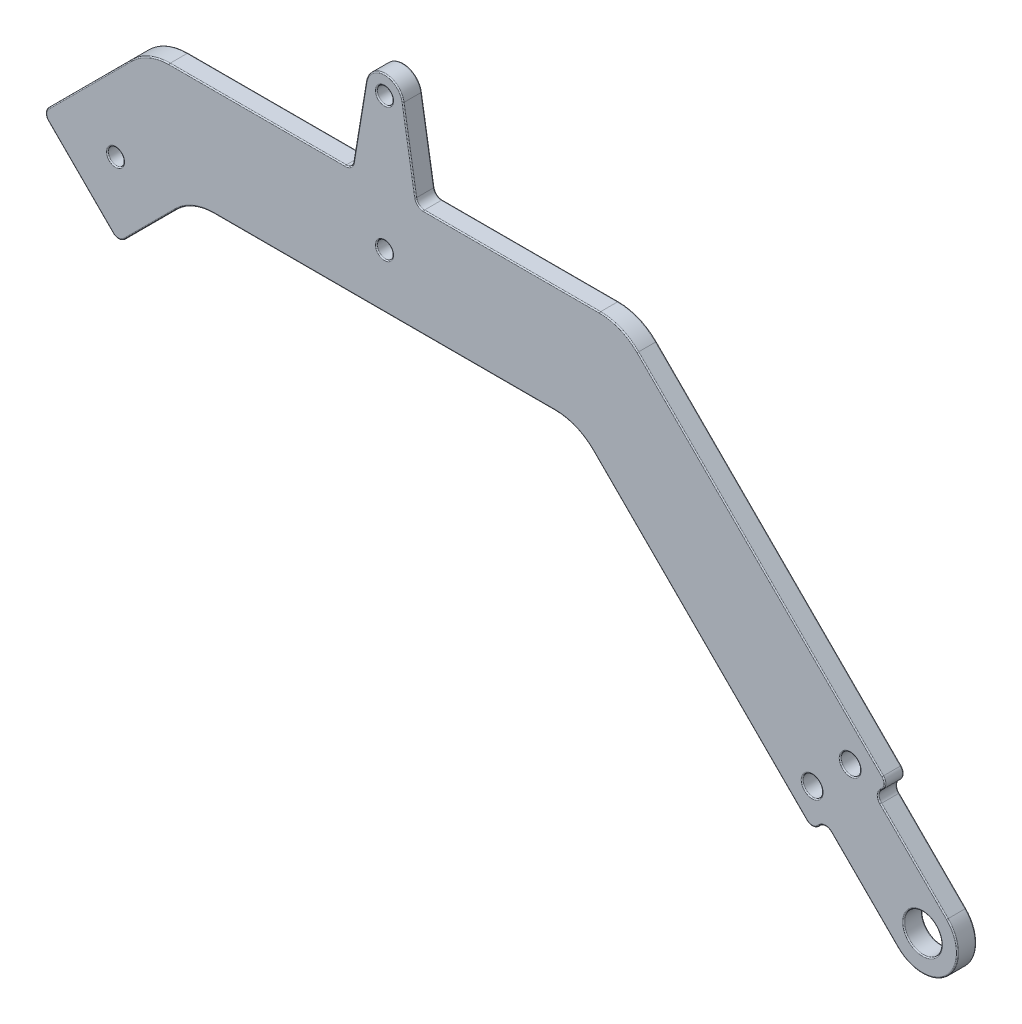
SolidWorks part; units mm, degrees
ref_plane "Front Plane" through (0, 0, 0) normal (0, 0, 1) x (1, 0, 0)
ref_plane "Top Plane" through (0, 0, 0) normal (0, 1, 0) x (1, 0, 0)
ref_plane "Right Plane" through (0, 0, 0) normal (1, 0, 0) x (0, 0, -1)
sketch "Sketch1" plane through (0, 0, 0) normal (0, 0, 1) x (1, 0, 0)
  line L0 (-100, 0) -> (100, 0) construction
  line L1 (-100, 0) -> (0, 100) construction
  line L2 (0, 100) -> (100, 0) construction
  line L3 (0, 0) -> (-50, 50) construction
  line L4 (-50, 50) -> (0, 0) construction
  line L5 (-40, 60) -> (40, 60) construction
  line L6 (0, 100) -> (0, 60) construction
  circle A0 centre (-100, 0) radius 20
  circle A1 centre (0, 0) radius 20
  circle A2 centre (100, 0) radius 20
  point P5 (0, 0)
  dimension "D5" = 40
  dimension "D1" = 200
  dimension "D2" = 90
  dimension "D3" = 90
  dimension "D4" = 80
sketch "Sketch2" plane through (0, 0, 0) normal (0, 0, 1) x (1, 0, 0)
  line L0 (-56.5165, 43.4835) -> (-40, 60) construction
  line L1 (-100, 0) -> (0, 100) construction
  line L2 (-40, 60) -> (40, 60) construction
  line L3 (40, 60) -> (86.565, 13.435) construction
  line L4 (0, 100) -> (100, 0) construction
  line L5 (-49.4454, 36.4124) -> (-35.8579, 50)
  line L6 (-35.8579, 50) -> (35.8579, 50)
  line L7 (35.8579, 50) -> (79.4939, 6.364)
  line L8 (-63.5876, 50.5546) -> (-44.1421, 70)
  line L9 (-44.1421, 70) -> (44.1421, 70)
  line L10 (44.1421, 70) -> (93.636, 20.5061)
  line L11 (-63.5876, 50.5546) -> (-49.4454, 36.4124)
  line L12 (93.636, 20.5061) -> (79.4939, 6.364)
  line L13 (81.9688, 8.8388) -> (95.4038, -4.5962)
  line L14 (91.1612, 18.0312) -> (104.5962, 4.5962)
  line L15 (75.9584, 9.8995) -> (90.1005, 24.0416) construction
  line L16 (0, 100) -> (0, 60) construction
  line L17 (-6, 70) -> (-3.4326, 85.5452)
  line L18 (6, 70) -> (3.4532, 85.4203)
  circle A0 centre (100, 0) radius 3.5
  circle A1 centre (100, 0) radius 10 construction
  arc A2 (95.4038, -4.5962) -> (104.5962, 4.5962) centre (100, 0) ccw
  circle A3 centre (100, 0) radius 0.5
  circle A4 centre (100, 0) radius 6.5 construction
  circle A5 centre (79.4939, 13.435) radius 1.8428
  circle A6 centre (86.565, 20.5061) radius 1.8428
  circle A7 centre (0, 60) radius 1.5
  circle A8 centre (0, 84.85) radius 1.5
  arc A9 (3.4532, 85.4203) -> (-3.4532, 85.4203) centre (0, 84.85) ccw
  circle A10 centre (0, 84.85) radius 3.5 construction
  circle A11 centre (-50, 50) radius 1.5
  dimension "D4" = 20
  dimension "D5" = 7
  dimension "D11" = 3
  dimension "D15" = 3
  dimension "D3" = 27.5
  dimension "D8" = 19
  dimension "D9" = 5
  dimension "D10" = 5
  dimension "5" = 5
  dimension "D12" = 14.85
  dimension "D7" = 6
  dimension "D14" = 6
  dimension "D1" = 10
  dimension "D2" = 10
  dimension "D6" = 3
  dimension "D13" = 2
sketch "Sketch3" plane through (0, 0, 0) normal (0, 0, 1) x (1, 0, 0)
  line L0 (-100, 0) -> (100, 0) construction
  line L1 (-86.6719, 13.3281) -> (-50, 50) construction
  line L2 (-24.0416, 9.8995) -> (-9.8995, 24.0416) construction
  line L3 (-50, 50) -> (-13.435, 13.435) construction
  line L4 (0, 0) -> (-50, 50) construction
  line L5 (-79.4939, 6.364) -> (-50, 35.8579)
  line L6 (-50, 35.8579) -> (-20.5061, 6.364)
  line L7 (-93.636, 20.5061) -> (-50, 64.1421)
  line L8 (-50, 64.1421) -> (-6.364, 20.5061)
  line L9 (-81.6799, 4.1779) -> (-50, 35.8579) construction
  line L10 (-95.8221, 18.3201) -> (-50, 64.1421) construction
  line L11 (-93.636, 20.5061) -> (-79.4939, 6.364)
  line L12 (-20.5061, 6.364) -> (-6.364, 20.5061)
  line L13 (-81.9688, 8.8388) -> (-95.4038, -4.5962)
  line L14 (-91.1612, 18.0312) -> (-104.5962, 4.5962)
  line L15 (-18.0312, 8.8388) -> (-4.5962, -4.5962)
  line L16 (-8.8388, 18.0312) -> (4.5962, 4.5962)
  line L17 (-88.751, 11.249) -> (-50, 50) construction
  line L18 (-90.1005, 24.0416) -> (-76.1469, 10.088) construction
  circle A0 centre (-100, 0) radius 10 construction
  circle A1 centre (-100, 0) radius 3.5
  circle A2 centre (0, 0) radius 10 construction
  circle A3 centre (0, 0) radius 3.5
  arc A4 (-4.5962, -4.5962) -> (4.5962, 4.5962) centre (0, 0) ccw
  arc A5 (-104.5962, 4.5962) -> (-95.4038, -4.5962) centre (-100, 0) ccw
  circle A6 centre (-86.565, 20.5061) radius 1
  circle A7 centre (0, 0) radius 6.5 construction
  circle A8 centre (-100, 0) radius 6.5 construction
  circle A9 centre (-79.4939, 13.435) radius 1
  circle A10 centre (-20.5061, 13.435) radius 1
  circle A11 centre (-13.435, 20.5061) radius 1
  circle A12 centre (-50, 50) radius 1.5 construction
  circle A13 centre (-50, 50) radius 1.5
  dimension "D1" = 20
  dimension "D2" = 7
  dimension "D9" = 2
  dimension "D7" = 19
  dimension "D8" = 19
  dimension "D10" = 5
  dimension "D11" = 5
  dimension "D12" = 5
  dimension "D13" = 5
  dimension "D14" = 5
  dimension "D15" = 5
  dimension "D3" = 3
  dimension "D4" = 3
  dimension "D5" = 10
  dimension "D6" = 10
sketch "Sketch4" plane through (0, 0, 0) normal (0, 0, 1) x (1, 0, 0)
  line L1 (57.5, 96.35) -> (57.5, 86.35)
  line L2 (57.5, 86.35) -> (44.1421, 70)
  line L3 (44.1421, 70) -> (-44.1421, 70)
  line L4 (-44.1421, 70) -> (-57.5, 86.35)
  line L5 (-57.5, 86.35) -> (-57.5, 96.35)
  line L7 (-57.5, 96.35) -> (57.5, 96.35)
  line L8 (-4, 60) -> (-4, 70)
  line L9 (4, 60) -> (4, 70)
  line L10 (-22.4799, 87.85) -> (22.5201, 87.85) construction
  line L11 (-22.4799, 92.35) -> (22.5201, 92.35)
  line L12 (-22.4799, 83.35) -> (22.5201, 83.35)
  circle A0 centre (0, 60) radius 1.5 construction
  circle A1 centre (0, 60) radius 1.5
  arc A2 (-4, 60) -> (4, 60) centre (0, 60) ccw
  circle A3 centre (0, 60) radius 4 construction
  arc A4 (-22.4799, 92.35) -> (-22.4799, 83.35) centre (-22.4799, 87.85) ccw
  arc A5 (22.5201, 83.35) -> (22.5201, 92.35) centre (22.5201, 87.85) ccw
  circle A6 centre (0, 84.85) radius 1.5 construction
  point P0 (0, 96.35)
  point P22 (0.0201, 87.85)
  dimension "D1" = 115
  dimension "D2" = 10
  dimension "D4" = 45
  dimension "D5" = 9
  dimension "D6" = 45
  dimension "D7" = 4
  dimension "D3" = 2.5
sketch "Sketch6" plane through (0, 0, 0) normal (0, 0, 1) x (1, 0, 0)
  line L0 (81.9688, 8.8388) -> (95.4038, -4.5962) construction
  line L1 (91.1612, 18.0312) -> (104.5962, 4.5962) construction
  line L2 (6, 70) -> (3.4532, 85.4203) construction
  line L3 (-6, 70) -> (-3.4326, 85.5452) construction
  line L4 (81.9688, 8.8388) -> (95.4038, -4.5962)
  line L5 (91.1612, 18.0312) -> (104.5962, 4.5962)
  line L6 (6, 70) -> (3.4532, 85.4203)
  line L7 (-6, 70) -> (-3.4326, 85.5452)
  line L8 (93.636, 20.5061) -> (44.1421, 70)
  line L9 (79.4939, 6.364) -> (93.636, 20.5061)
  line L10 (35.8579, 50) -> (79.4939, 6.364)
  line L11 (-35.8579, 50) -> (35.8579, 50)
  line L12 (-49.4454, 36.4124) -> (-35.8579, 50)
  line L13 (-63.5876, 50.5546) -> (-49.4454, 36.4124)
  line L14 (-44.1421, 70) -> (-63.5876, 50.5546)
  line L15 (44.1421, 70) -> (-44.1421, 70)
  line L16 (93.636, 20.5061) -> (44.1421, 70)
  line L17 (79.4939, 6.364) -> (81.9688, 8.8388)
  line L18 (35.8579, 50) -> (79.4939, 6.364)
  line L19 (-35.8579, 50) -> (35.8579, 50)
  line L20 (-49.4454, 36.4124) -> (-35.8579, 50)
  line L21 (-63.5876, 50.5546) -> (-49.4454, 36.4124)
  line L22 (-44.1421, 70) -> (-63.5876, 50.5546)
  line L23 (44.1421, 70) -> (6, 70)
  line L24 (-6, 70) -> (-44.1421, 70)
  line L25 (91.1612, 18.0312) -> (93.636, 20.5061)
  arc A0 (95.4038, -4.5962) -> (104.5962, 4.5962) centre (100, 0) ccw construction
  circle A1 centre (100, 0) radius 0.5
  circle A2 centre (100, 0) radius 0.5
  circle A3 centre (100, 0) radius 3.5
  circle A4 centre (100, 0) radius 3.5
  circle A5 centre (0, 84.85) radius 1.5
  circle A6 centre (0, 84.85) radius 1.5
  circle A7 centre (0, 60) radius 1.5
  circle A8 centre (0, 60) radius 1.5
  circle A9 centre (86.565, 20.5061) radius 1.8428
  circle A10 centre (86.565, 20.5061) radius 1.8428
  circle A11 centre (79.4939, 13.435) radius 1.8428
  circle A12 centre (79.4939, 13.435) radius 1.8428
  circle A13 centre (-50, 50) radius 1.5
  circle A14 centre (-50, 50) radius 1.5
  arc A15 (3.4532, 85.4203) -> (-3.4532, 85.4203) centre (0, 84.85) ccw construction
  arc A16 (95.4038, -4.5962) -> (104.5962, 4.5962) centre (100, 0) ccw
  arc A17 (3.4532, 85.4203) -> (-3.4532, 85.4203) centre (0, 84.85) ccw
  dimension "D1" = 0
  dimension "D2" = 0
  dimension "D3" = 0
  dimension "D4" = 0
  dimension "D5" = 0
  dimension "D6" = 0
  dimension "D7" = 0
  dimension "D8" = 0
extrude "Boss-Extrude1" add sketch "Sketch6" along normal blind 3.5 contours L6 A17 L7 L24 L22 L21 L20 L19 L18 L17 L4 A16 L5 L25 L16 L23 A4 A6 A8 A10 A12 A14
fillet "Fillet1" radius 10 4 edges at (-35.8579, 50, 1.75) (35.8579, 50, 1.75) (-44.1421, 70, 1.75) (44.1421, 70, 1.75)
fillet "Fillet2" radius 1.5 8 edges at (-49.4454, 36.4124, 1.75) (-63.5876, 50.5546, 1.75) (-6, 70, 1.75) (6, 70, 1.75) (81.9688, 8.8388, 1.75) (79.4939, 6.364, 1.75) (91.1612, 18.0312, 1.75) (93.636, 20.5061, 1.75)
fillet "Fillet3" radius 0.2 68 edges at (103.5, 0, 0) (1.5, 84.85, 0) (1.5, 60, 0) (88.4078, 20.5061, 0) (81.3367, 13.435, 0) (-48.5, 50, 0) (4.6229, 78.3379, 0) (0, 88.35, 0) (-4.6229, 78.3379, 0) (-23.6363, 70, 0) (-54.799, 59.3431, 0) (-56.5165, 43.4835, 0) (-43.5858, 42.2721, 0) (0, 50, 0) (58.61, 27.2478, 0) (80.7313, 7.6014, 0) (89.2166, 1.591, 0) (104.5962, -4.5962, 0) (98.409, 10.7834, 0) (92.3986, 19.2687, 0) (69.8232, 44.3189, 0) (23.6363, 70, 0) (103.5, 0, 3.5) (1.5, 84.85, 3.5) (1.5, 60, 3.5) (88.4078, 20.5061, 3.5) (81.3367, 13.435, 3.5) (-48.5, 50, 3.5) (4.6229, 78.3379, 3.5) (0, 88.35, 3.5) (-4.6229, 78.3379, 3.5) (-23.6363, 70, 3.5) (-54.799, 59.3431, 3.5) (-56.5165, 43.4835, 3.5) (-43.5858, 42.2721, 3.5) (0, 50, 3.5) (58.61, 27.2478, 3.5) (80.7313, 7.6014, 3.5) (89.2166, 1.591, 3.5) (104.5962, -4.5962, 3.5) (98.409, 10.7834, 3.5) (92.3986, 19.2687, 3.5) (69.8232, 44.3189, 3.5) (43.8268, 69.2388, 0) (-43.8268, 69.2388, 0) (43.8268, 69.2388, 3.5) (-43.8268, 69.2388, 3.5) (-35.5426, 49.2388, 0) (-35.5426, 49.2388, 3.5) (35.5426, 49.2388, 0) (35.5426, 49.2388, 3.5) (93.0147, 20.5061, 0) (79.4939, 6.9853, 0) (-62.9663, 50.5546, 0) (-49.4454, 37.0337, 0) (93.0147, 20.5061, 3.5) (79.4939, 6.9853, 3.5) (-62.9663, 50.5546, 3.5) (-49.4454, 37.0337, 3.5) (-6.3022, 70.3562, 0) (-6.3022, 70.3562, 3.5) (6.3022, 70.3562, 0) (6.3022, 70.3562, 3.5) (81.9688, 8.2175, 0) (81.9688, 8.2175, 3.5) (91.7825, 18.0312, 0) (91.7825, 18.0312, 3.5) (23.6363, 70, 3.5)
